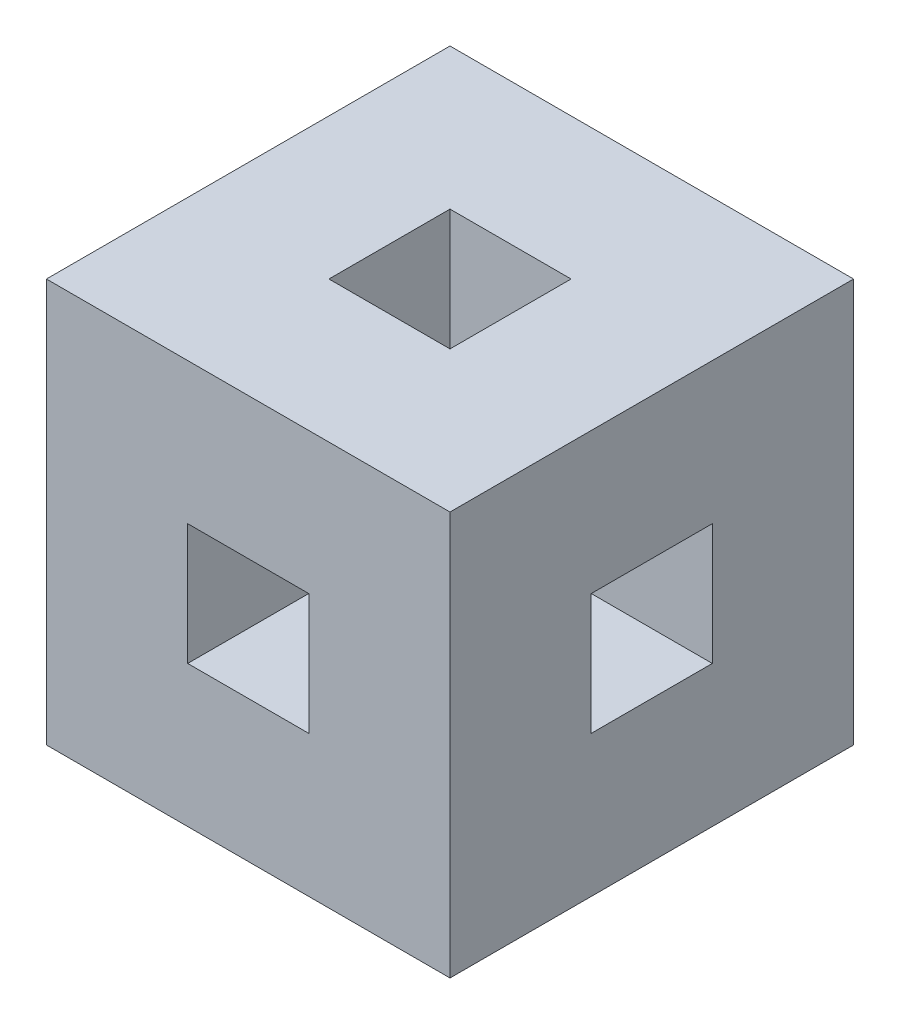
SolidWorks part; units mm, degrees
ref_plane "Front Plane" through (0, 0, 0) normal (0, 0, 1) x (1, 0, 0)
ref_plane "Top Plane" through (0, 0, 0) normal (0, 1, 0) x (1, 0, 0)
ref_plane "Right Plane" through (0, 0, 0) normal (1, 0, 0) x (0, 0, -1)
sketch "Sketch2" plane through (0, 0, 0) normal (0, 1, 0) x (1, 0, 0)
  line L1 (-25, -25) -> (25, -25)
  line L2 (-25, -25) -> (-25, 25)
  line L3 (-25, 25) -> (25, 25)
  line L4 (25, -25) -> (25, 25)
  line L5 (-25, -25) -> (25, 25) construction
  line L6 (-25, 25) -> (25, -25) construction
  point P0 (0, 0)
  dimension "D1" = 50
  dimension "D2" = 50
extrude "Boss-Extrude1" add sketch "Sketch2" along normal blind 50
sketch "Sketch4" plane through (0, 0, 25) normal (0, 0, 1) x (1, 0, 0)
  line L0 (-25, 50) -> (-25, 0) construction
  line L1 (-7.5, 17.5) -> (7.5, 17.5)
  line L2 (-7.5, 17.5) -> (-7.5, 32.5)
  line L3 (-7.5, 32.5) -> (7.5, 32.5)
  line L4 (7.5, 17.5) -> (7.5, 32.5)
  line L5 (-7.5, 17.5) -> (7.5, 32.5) construction
  line L6 (-7.5, 32.5) -> (7.5, 17.5) construction
  line L7 (-25, 50) -> (25, 50) construction
  point P0 (0, 25)
  point P7 (0, 0)
  dimension "D1" = 15
  dimension "D2" = 15
  dimension "D3" = 25
  dimension "D4" = 25
extrude "Cut-Extrude1" cut sketch "Sketch4" against normal through all contours L2 L1 L4 L3
sketch "Sketch5" plane through (25, 0, 0) normal (1, 0, 0) x (0, 0, -1)
  line L0 (-7.5, 17.5) -> (7.5, 17.5)
  line L1 (-7.5, 17.5) -> (-7.5, 32.5)
  line L2 (-7.5, 32.5) -> (7.5, 32.5)
  line L3 (7.5, 17.5) -> (7.5, 32.5)
  line L4 (-7.5, 17.5) -> (7.5, 32.5) construction
  line L5 (-7.5, 32.5) -> (7.5, 17.5) construction
  line L6 (-25, 50) -> (-25, 0) construction
  line L7 (-25, 50) -> (25, 50) construction
  point P0 (0, 25)
  dimension "D1" = 15
  dimension "D2" = 15
  dimension "D3" = 25
  dimension "D4" = 25
extrude "Cut-Extrude2" cut sketch "Sketch5" against normal through all contours L0 L3 L2 L1
sketch "Sketch6" plane through (0, 50, 0) normal (0, 1, 0) x (1, 0, 0)
  line L0 (-7.5, -7.5) -> (7.5, -7.5)
  line L1 (-7.5, -7.5) -> (-7.5, 7.5)
  line L2 (-7.5, 7.5) -> (7.5, 7.5)
  line L3 (7.5, -7.5) -> (7.5, 7.5)
  line L4 (-7.5, -7.5) -> (7.5, 7.5) construction
  line L5 (-7.5, 7.5) -> (7.5, -7.5) construction
  line L6 (-25, 25) -> (-25, -25) construction
  line L7 (25, 25) -> (-25, 25) construction
  point P0 (0, 0)
  point P7 (0, 0)
  point P9 (-3.5914, 5.6026)
  dimension "D1" = 15
  dimension "D2" = 15
  dimension "D3" = 25
  dimension "D4" = 25
extrude "Cut-Extrude3" cut sketch "Sketch6" against normal through all contours L0 L3 L2 L1
